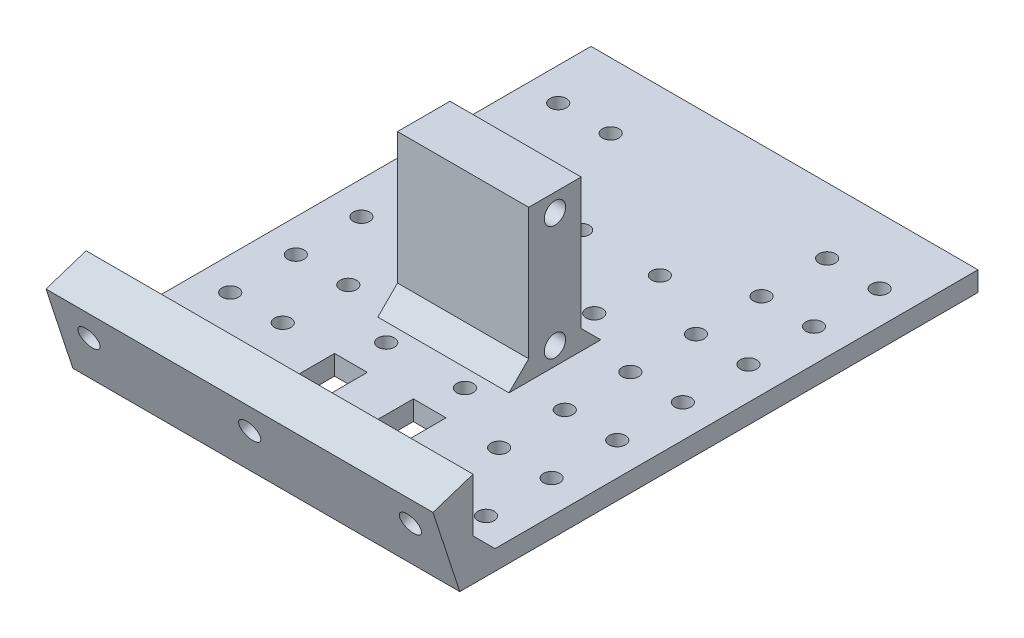
SolidWorks part; units mm, degrees
ref_plane "Alzado" through (0, 0, 0) normal (0, 0, 1) x (1, 0, 0)
ref_plane "Planta" through (0, 0, 0) normal (0, 1, 0) x (1, 0, 0)
ref_plane "Vista lateral" through (0, 0, 0) normal (1, 0, 0) x (0, 0, -1)
sketch "Croquis1" plane through (0, 0, 0) normal (0, 1, 0) x (1, 0, 0)
  line L0 (-29.5, 32.6406) -> (29.5, 32.6406)
  line L1 (29.5, 32.6406) -> (29.5, -47.3594)
  line L2 (29.5, -47.3594) -> (8.5, -47.3594)
  line L3 (8.5, -47.3594) -> (8.5, -27.4531)
  line L4 (8.5, -27.4531) -> (3.5, -27.4531)
  line L5 (3.5, -27.4531) -> (3.5, -47.3594)
  line L6 (3.5, -47.3594) -> (-3.5, -47.3594)
  line L7 (-3.5, -47.3594) -> (-3.5, -27.4531)
  line L8 (-3.5, -27.4531) -> (-8.5, -27.4531)
  line L9 (-8.5, -27.4531) -> (-8.5, -47.3594)
  line L10 (-8.5, -47.3594) -> (-29.5, -47.3594)
  line L11 (-29.5, -47.3594) -> (-29.5, 32.6406)
  line L12 (2, -7.3594) -> (47.9375, -7.3594) construction
  line L13 (0, 0) -> (0, 41.2344) construction
  dimension "D1" = 3.5
  dimension "D2" = 3.5
  dimension "D3" = 5
  dimension "D4" = 5
  dimension "D5" = 21
  dimension "D6" = 21
  dimension "D7" = 40
  dimension "D8" = 40
extrude "Saliente-Extruir1" add sketch "Croquis1" along normal blind 3
sketch "Sketch1" plane through (0, 3, 0) normal (0, 1, 0) x (1, 0, 0)
  line L0 (29.5, 32.6406) -> (-29.5, 32.6406) construction
  line L1 (-10, 23.1406) -> (10, 23.1406)
  line L2 (-10, 23.1406) -> (-10, 16.1406)
  line L3 (-10, 16.1406) -> (10, 16.1406)
  line L4 (10, 23.1406) -> (10, 16.1406)
  line L5 (-10, -8.3594) -> (10, -8.3594)
  line L6 (-10, -8.3594) -> (-10, -16.3594)
  line L7 (-10, -16.3594) -> (10, -16.3594)
  line L8 (10, -8.3594) -> (10, -16.3594)
  line L9 (0, 32.6406) -> (0, -23.7131) construction
  line L10 (8.5, -47.3594) -> (29.5, -47.3594) construction
  line L11 (3.5, -16.3594) -> (-3.5, -16.3594)
  line L12 (3.5, -16.3594) -> (3.5, -54.8594)
  line L13 (3.5, -54.8594) -> (-3.5, -54.8594)
  line L14 (-3.5, -16.3594) -> (-3.5, -54.8594)
  dimension "D1" = 9.5
  dimension "D2" = 7
  dimension "D3" = 10
  dimension "D4" = 10
  dimension "D5" = 24.5
  dimension "D6" = 8
  dimension "D7" = 10
  dimension "D8" = 10
  dimension "D9" = 7.5
extrude "Boss-Extrude1" add sketch "Sketch1" along normal blind 23 contours L9 L5 L6 L7 | L5 L9 L11 L7 L8 | L1 L9 L3 L4 | L9 L1 L2 L3
sketch "Sketch2" plane through (29.5, 0, 0) normal (1, 0, 0) x (0, 0, -1)
  line L0 (-54.8594, 26) -> (-46.3594, 0)
  line L1 (-47.3594, 0) -> (32.6406, 0) construction
  line L2 (-47.3594, 0) -> (-46.3594, 0)
  line L3 (-47.3594, 0) -> (-47.3594, 3)
  line L4 (-47.3594, 3) -> (-54.8594, 3)
  line L5 (-54.8594, 26) -> (-54.8594, 3)
  dimension "D1" = 1
extrude "Cut-Extrude1" cut sketch "Sketch2" against normal through all
sketch "Sketch3" plane through (-10, 0, 0) normal (-1, 0, 0) x (0, 0, 1)
  line L0 (8.3594, 3) -> (16.3594, 3) construction
  line L1 (16.3594, 26) -> (16.3594, 3) construction
  circle A0 centre (12.3594, 5.75) radius 1.625
  circle A1 centre (12.3594, 23.25) radius 1.625
  dimension "D1" = 3.25
  dimension "D2" = 3.25
  dimension "D3" = 2.75
  dimension "D4" = 4
  dimension "D5" = 17.5
extrude "Cut-Extrude2" cut sketch "Sketch3" against normal through all
sketch "Croquis2" plane through (0, 0, -23.1406) normal (0, 0, -1) x (-1, 0, 0)
  line L0 (-10, 26) -> (-10, 3) construction
  line L1 (-5, 6) -> (-5, 3)
  line L2 (-5, 6) -> (-5, 21)
  line L3 (-5, 21) -> (5, 21)
  line L4 (5, 6) -> (5, 21)
  line L5 (10, 26) -> (10, 3) construction
  line L6 (10, 26) -> (-10, 26) construction
  line L7 (10, 3) -> (-10, 3) construction
  line L8 (5, 6) -> (5, 3)
  line L9 (5, 3) -> (-5, 3)
  dimension "D1" = 5
  dimension "D2" = 5
  dimension "D3" = 5
  dimension "D4" = 3
extrude "Cortar-Extruir1" cut sketch "Croquis2" against normal blind 10
sketch "Croquis3" plane through (-3.5, 0, 0) normal (-1, 0, 0) x (0, 0, 1)
  line L1 (21.9062, 3) -> (36.9062, 3)
  line L2 (21.9062, 26) -> (16.3594, 26)
  line L3 (21.9062, 26) -> (36.9062, 26)
  line L4 (36.9062, 3) -> (36.9062, 26)
  line L5 (16.3594, 26) -> (54.8594, 26) construction
  line L7 (16.3594, 26) -> (16.3594, 3)
  line L8 (16.3594, 3) -> (21.9062, 3)
  dimension "D1" = 15
extrude "Cortar-Extruir2" cut sketch "Croquis3" against normal up to next
sketch "Croquis4" plane through (0, 0, 0) normal (0, -1, 0) x (1, 0, 0)
  line L0 (-29.5, -32.6406) -> (-29.5, 46.3594) construction
  line L1 (29.5, -32.6406) -> (-29.5, -32.6406) construction
  line L2 (0, -32.6406) -> (0, 46.3594) construction
  line L4 (-10, 8.3594) -> (10, 8.3594) construction
  circle A0 centre (-24.5, -22.6406) radius 1.25
  circle A1 centre (-16.5, -22.6406) radius 1.25
  circle A2 centre (-16.5, -12.6406) radius 1.25
  circle A3 centre (-16.5, -2.6406) radius 1.25
  circle A4 centre (-16.5, 7.3594) radius 1.25
  circle A5 centre (-16.5, 17.3594) radius 1.25
  circle A6 centre (-16.5, 27.3594) radius 1.25
  circle A7 centre (-16.5, 37.3594) radius 1.25
  circle A8 centre (-24.5, -12.6406) radius 1.25
  circle A9 centre (-24.5, -2.6406) radius 1.25
  circle A10 centre (-24.5, 7.3594) radius 1.25
  circle A11 centre (-24.5, 17.3594) radius 1.25
  circle A12 centre (-24.5, 27.3594) radius 1.25
  circle A13 centre (-24.5, 37.3594) radius 1.25
  circle A14 centre (16.5, 37.3594) radius 1.25
  circle A15 centre (24.5, 37.3594) radius 1.25
  circle A16 centre (16.5, 27.3594) radius 1.25
  circle A17 centre (24.5, 27.3594) radius 1.25
  circle A18 centre (16.5, 17.3594) radius 1.25
  circle A19 centre (24.5, 17.3594) radius 1.25
  circle A20 centre (24.5, 7.3594) radius 1.25
  circle A21 centre (16.5, 7.3594) radius 1.25
  circle A22 centre (16.5, -2.6406) radius 1.25
  circle A23 centre (24.5, -2.6406) radius 1.25
  circle A24 centre (24.5, -12.6406) radius 1.25
  circle A25 centre (16.5, -12.6406) radius 1.25
  circle A26 centre (16.5, -22.6406) radius 1.25
  circle A27 centre (24.5, -22.6406) radius 1.25
  circle A28 centre (6, 22.0845) radius 1.25
  circle A29 centre (-6, 22.0845) radius 1.25
  circle A30 centre (6, 2.3594) radius 1.25
  circle A31 centre (-6, 2.3594) radius 1.25
  circle A32 centre (-6, -7.6406) radius 1.25
  circle A33 centre (6, -7.6406) radius 1.25
  dimension "D1" = 2.5
  dimension "D6" = 2.5
  dimension "D8" = 2.5
  dimension "D2" = 5
  dimension "D3" = 10
  dimension "D7" = 6
  dimension "D9" = 6
  dimension "D4" = 2
  dimension "D5" = 7
  dimension "D10" = 2
  dimension "D11" = 2
extrude "Cortar-Extruir3" cut sketch "Croquis4" against normal up to next (3 mm away)
sketch "Sketch5" plane through (-8.5, 0, 0) normal (1, 0, 0) x (0, 0, -1)
  line L0 (-36.9062, 3) -> (-36.9062, 0)
  line L1 (-46.3594, 0) -> (32.6406, 0) construction
  line L2 (-36.9062, 0) -> (-46.3594, 0)
  line L3 (-46.3594, 0) -> (-47.3401, 3)
  line L4 (-47.3401, 3) -> (-36.9062, 3)
extrude "Boss-Extrude2" add sketch "Sketch5" along normal blind 20
sketch "Croquis6" plane through (-29.5, 0, 0) normal (-1, 0, 0) x (0, 0, 1)
  line L0 (47.3401, 3) -> (50.4475, 12.505)
  line L1 (47.3401, 3) -> (54.8594, 26) construction
  line L2 (50.4475, 12.505) -> (44.3401, 14.5016)
  line L3 (44.3401, 14.5016) -> (44.3401, 3)
  line L4 (47.3401, 3) -> (36.9062, 3) construction
  line L5 (44.3401, 3) -> (47.3401, 3)
  line L6 (44.3401, 6.348) -> (40.9901, 3)
  line L7 (-32.6406, 3) -> (47.3401, 3) construction
  line L8 (40.9901, 3) -> (44.3401, 3)
  line L9 (48.8938, 7.7525) -> (39.3394, 10.876) construction
  line L10 (44.3401, 6.348) -> (45.1947, 8.9618) construction
  line M3 (47.3401, 3) -> (-32.6406, 3)
  dimension "D1" = 10
  dimension "D2" = 3
  dimension "D3" = 2.75
  dimension "D4" = 3.348
  dimension "D5" = 3.35
extrude "Saliente-Extruir2" add sketch "Croquis6" against normal up to vertex (59 mm away) contours L2 L3 L0 M3 | L3 L6 M3
sketch "Croquis7" plane through (0, -13.6925, 41.883) normal (0, -0.3107, 0.9505) x (1, 0, 0)
  circle A0 centre (-24.5, 22.5619) radius 1.625
  dimension "D1" = 3.25
extrude "Cortar-Extruir4" cut sketch "Croquis7" against normal up to next
sketch "Croquis8" plane through (0, -13.6925, 41.883) normal (0, -0.3107, 0.9505) x (1, 0, 0)
  line L1 (-22.9123, 19.8119) -> (-21.3246, 22.5619)
  line L2 (-21.3246, 22.5619) -> (-22.9123, 25.3119)
  line L3 (-22.9123, 25.3119) -> (-26.0877, 25.3119)
  line L4 (-26.0877, 25.3119) -> (-27.6754, 22.5619)
  line L5 (-27.6754, 22.5619) -> (-26.0877, 19.8119)
  line L6 (-26.0877, 19.8119) -> (-22.9123, 19.8119)
  circle A0 centre (-24.5, 22.5619) radius 2.75 construction
  dimension "D1" = 5.5
extrude "Cortar-Extruir5" cut sketch "Croquis8" along normal blind 4 from vertex at -2.4255
sketch "Croquis16" plane through (10, 0, 0) normal (1, 0, 0) x (0, 0, -1)
  line L0 (-8.3594, 6) -> (-5.3594, 3)
  line L1 (-8.3594, 26) -> (-8.3594, 3) construction
  line L2 (-40.9901, 3) -> (32.6406, 3) construction
  line L3 (-5.3594, 3) -> (-8.3594, 3)
  line L4 (-8.3594, 3) -> (-8.3594, 6)
  line L5 (-12.3594, 7.375) -> (-12.3594, 12.3277) construction
  line L6 (-19.3594, 3) -> (-16.3594, 3)
  line L7 (-16.3594, 6) -> (-19.3594, 3)
  line L8 (-16.3594, 3) -> (-16.3594, 6)
  dimension "D1" = 3
  dimension "D2" = 3
extrude "Saliente-Extruir4" add sketch "Croquis16" against normal up to vertex
sketch "Croquis17" plane through (-10, 0, 0) normal (-1, 0, 0) x (0, 0, 1)
  line L1 (-16.1406, 26) -> (-23.1406, 26)
  line L2 (-16.1406, 26) -> (-16.1406, 3)
  line L3 (-16.1406, 3) -> (-23.1406, 3)
  line L4 (-23.1406, 26) -> (-23.1406, 3)
extrude "Cortar-Extruir11" cut sketch "Croquis17" against normal through all
sketch "Local Files1" plane through (-29.5, 0, 0) normal (-1, 0, 0) x (0, 0, 1)
  line L0 (36.9062, 3) -> (40.9901, 3)
  line L1 (40.9901, 3) -> (44.3401, 6.348)
  line L2 (44.3401, 6.348) -> (44.3401, 14.5016)
  line L3 (44.3401, 14.5016) -> (50.4475, 12.505)
  line L4 (50.4475, 12.505) -> (54.8594, 26)
  line L5 (54.8594, 26) -> (36.9062, 26)
  line L6 (36.9062, 26) -> (36.9062, 3)
extrude "Cut-Extrude3" cut sketch "Local Files1" against normal through all
sketch "Local Files2" plane through (0, -13.6925, 41.883) normal (0, -0.3107, 0.9505) x (1, 0, 0)
  line L0 (-24.5, 22.5619) -> (22.993, 22.5619) construction
  line L1 (0, 22.5619) -> (0, 14.4057) construction
  circle A0 centre (0, 22.5619) radius 1.625
  circle A1 centre (-24.5, 22.5619) radius 1.625
  circle A2 centre (24.5, 22.5619) radius 1.625
  dimension "D1" = 3.25
  dimension "D2" = 24.5
extrude "Cut-Extrude4" cut sketch "Local Files2" against normal blind 10
sketch "Local Files4" plane through (0, -13.6925, 41.883) normal (0, -0.3107, 0.9505) x (1, 0, 0)
  line L1 (1.5877, 19.8119) -> (3.1754, 22.5619)
  line L2 (3.1754, 22.5619) -> (1.5877, 25.3119)
  line L3 (1.5877, 25.3119) -> (-1.5877, 25.3119)
  line L4 (-1.5877, 25.3119) -> (-3.1754, 22.5619)
  line L5 (-3.1754, 22.5619) -> (-1.5877, 19.8119)
  line L6 (-1.5877, 19.8119) -> (1.5877, 19.8119)
  line L7 (26.0877, 19.8119) -> (27.6754, 22.5619)
  line L8 (27.6754, 22.5619) -> (26.0877, 25.3119)
  line L9 (26.0877, 25.3119) -> (22.9123, 25.3119)
  line L10 (22.9123, 25.3119) -> (21.3246, 22.5619)
  line L11 (21.3246, 22.5619) -> (22.9123, 19.8119)
  line L12 (22.9123, 19.8119) -> (26.0877, 19.8119)
  circle A0 centre (0, 22.5619) radius 2.75 construction
  circle A1 centre (24.5, 22.5619) radius 2.75 construction
  dimension "D1" = 5.5
  dimension "D2" = 5.5
extrude "Cut-Extrude5" cut sketch "Local Files4" along normal blind 4 from vertex at -2.4255
